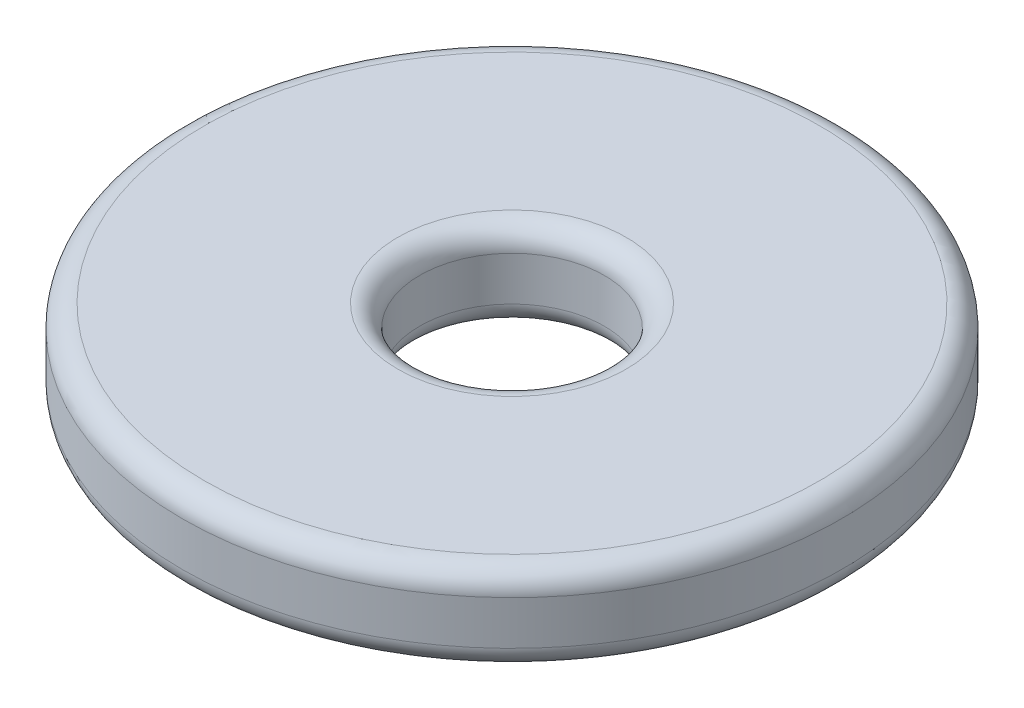
SolidWorks part; units mm, degrees
ref_plane "Front Plane" through (0, 0, 0) normal (0, 0, 1) x (1, 0, 0)
ref_plane "Top Plane" through (0, 0, 0) normal (0, 1, 0) x (1, 0, 0)
ref_plane "Right Plane" through (0, 0, 0) normal (1, 0, 0) x (0, 0, -1)
sketch "Sketch1" plane through (0, 0, 0) normal (0, 1, 0) x (1, 0, 0)
  circle A0 centre (0, 0) radius 2.1
  circle A1 centre (0, 0) radius 7.5
  dimension "D1" = 4.2
  dimension "D2" = 15
extrude "Boss-Extrude1" add sketch "Sketch1" along normal blind 2
fillet "Fillet1" radius 0.5 4 edges at (0, 0, 2.1) (0, 2, 2.1) (0, 0, 7.5) (0, 2, 7.5)
